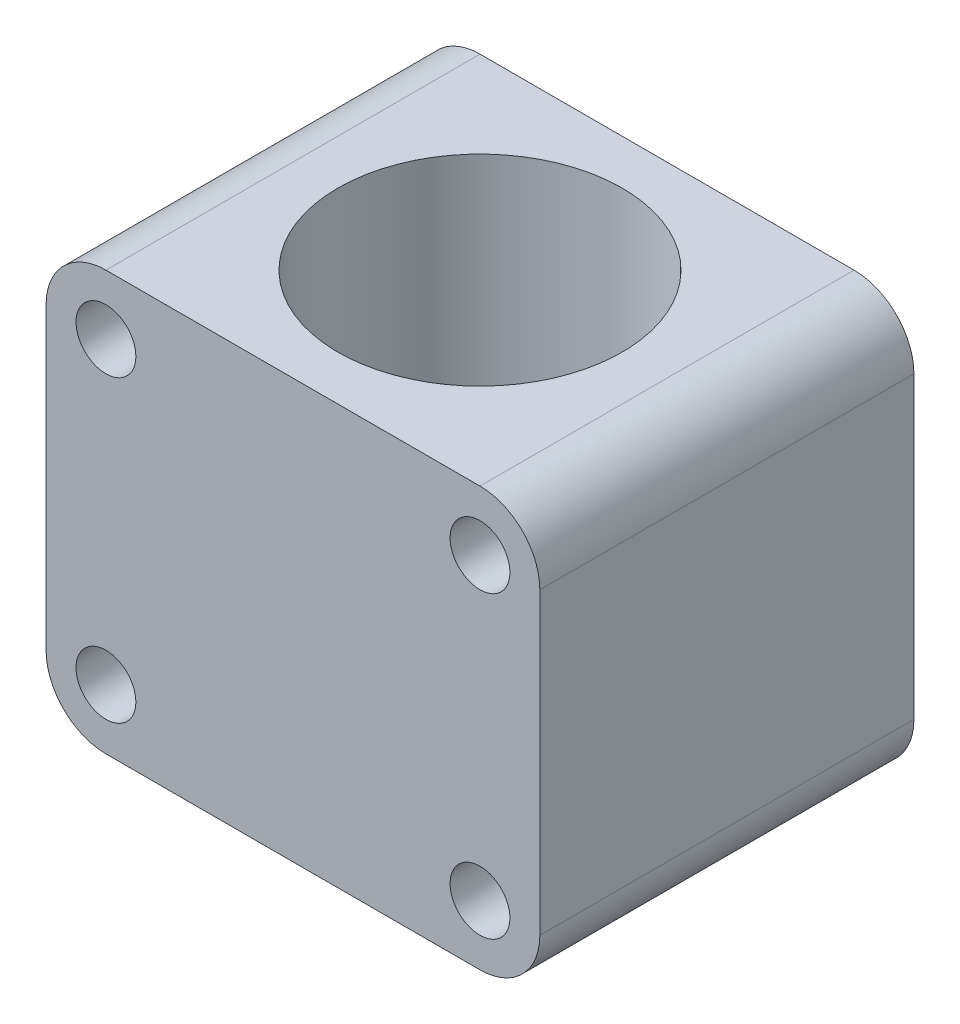
SolidWorks part; units mm, degrees
ref_plane "前视基准面" through (0, 0, 0) normal (0, 0, 1) x (1, 0, 0)
ref_plane "上视基准面" through (0, 0, 0) normal (0, 1, 0) x (1, 0, 0)
ref_plane "右视基准面" through (0, 0, 0) normal (1, 0, 0) x (0, 0, -1)
other "Configuration Table"
sketch "草图1" plane through (0, 0, 0) normal (0, 0, 1) x (1, 0, 0)
  line L1 (-16.5, 14) -> (16.5, 14)
  line L2 (-16.5, 14) -> (-16.5, -14)
  line L3 (-16.5, -14) -> (16.5, -14)
  line L4 (16.5, 14) -> (16.5, -14)
  line L5 (-16.5, 14) -> (16.5, -14) construction
  line L6 (-16.5, -14) -> (16.5, 14) construction
  line L7 (-12.5, 10) -> (12.5, 10) construction
  line L8 (-12.5, 10) -> (-12.5, -10) construction
  line L9 (-12.5, -10) -> (12.5, -10) construction
  line L10 (12.5, 10) -> (12.5, -10) construction
  line L11 (-12.5, 10) -> (12.5, -10) construction
  line L12 (-12.5, -10) -> (12.5, 10) construction
  circle A0 centre (12.5, -10) radius 2
  circle A1 centre (-12.5, -10) radius 2
  circle A2 centre (-12.5, 10) radius 2
  circle A3 centre (12.5, 10) radius 2
  point P0 (0, 0)
  point P6 (0, 0)
  point P15 (0, 0)
  dimension "D5" = 4
  dimension "D1" = 28
  dimension "D2" = 33
  dimension "D3" = 20
  dimension "D4" = 25
extrude "凸台-拉伸1" add sketch "草图1" along normal blind 25
fillet "圆角1" radius 4 4 edges at (-16.5, -14, 12.5) (-16.5, 14, 12.5) (16.5, -14, 12.5) (16.5, 14, 12.5)
sketch "草图2" plane through (0, 14, 0) normal (0, 1, 0) x (1, 0, 0)
  circle A0 centre (0, -12.5) radius 9.5
  dimension "D1" = 19
extrude "切除-拉伸1" cut sketch "草图2" against normal through all
